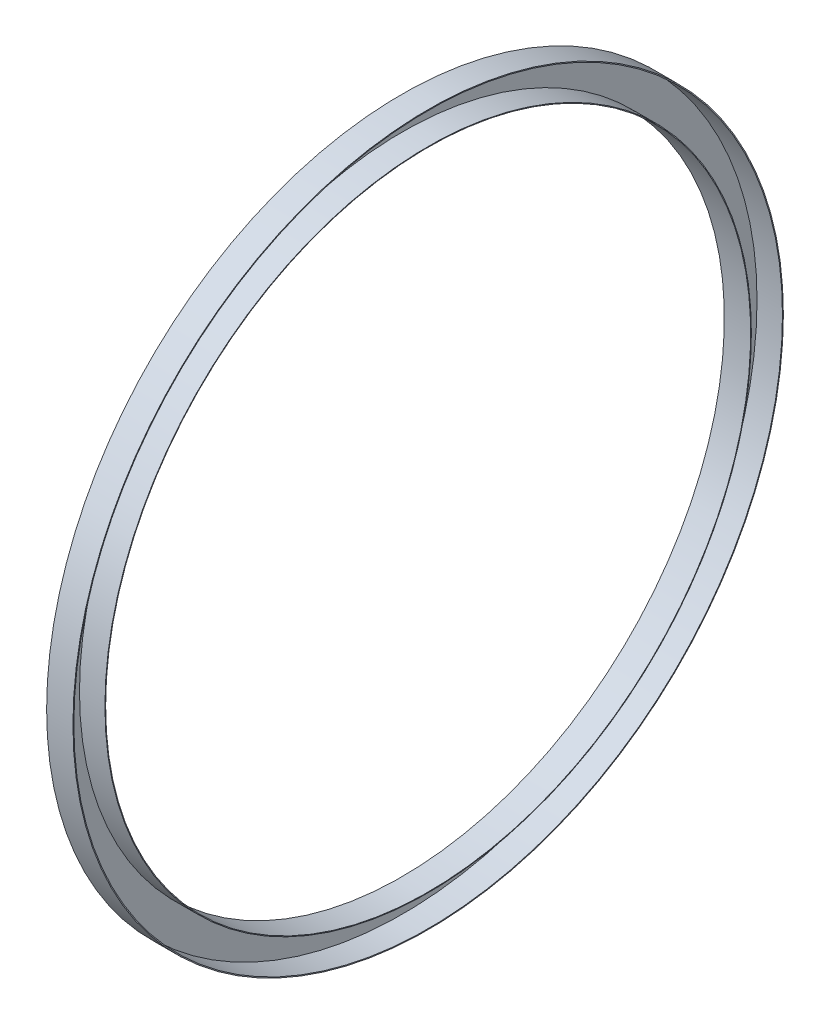
SolidWorks part; units mm, degrees
ref_plane "Front Plane" through (0, 0, 0) normal (0, 0, 1) x (1, 0, 0)
ref_plane "Top Plane" through (0, 0, 0) normal (0, 1, 0) x (1, 0, 0)
ref_plane "Right Plane" through (0, 0, 0) normal (1, 0, 0) x (0, 0, -1)
sketch "Sketch1" plane through (0, 0, 0) normal (0, 0, 1) x (1, 0, 0)
  line L0 (0, 102.8429) -> (0, 93.3761)
  line L1 (-297.0545, 0) -> (386.8634, 0) construction
  line L3 (7.62, 93.584) -> (7.62, 93.3761)
  line L5 (7.62, 102.8429) -> (7.62, 102.5784)
  line L7 (7.62, 93.584) -> (0.2561, 93.584)
  line L9 (0, 93.3761) -> (7.62, 93.3761)
  line L10 (7.62, 102.8429) -> (7.62, 102.5784)
  line L11 (7.62, 93.584) -> (7.62, 93.3761)
  line L12 (7.62, 102.5784) -> (0.2561, 102.5784)
  line L13 (0, 102.8429) -> (7.62, 102.8429)
  line L15 (7.62, 102.8429) -> (7.62, 102.5784)
  line L16 (7.62, 102.5784) -> (0.2561, 102.5784)
  line L17 (0.2561, 102.5784) -> (0.2561, 93.584)
  line L18 (0.2561, 93.584) -> (7.62, 93.584)
  line L19 (7.62, 93.584) -> (7.62, 93.3761)
  line L20 (7.62, 93.3761) -> (0, 93.3761)
  line L21 (0, 93.3761) -> (0, 102.8429)
  line L22 (7.62, 102.8429) -> (7.62, 102.5784)
revolve "Revolve1" add sketch "Sketch1" angle 360 about L1
scale "Scale1" scale about centroid uniform scaling yes scale factor 12
